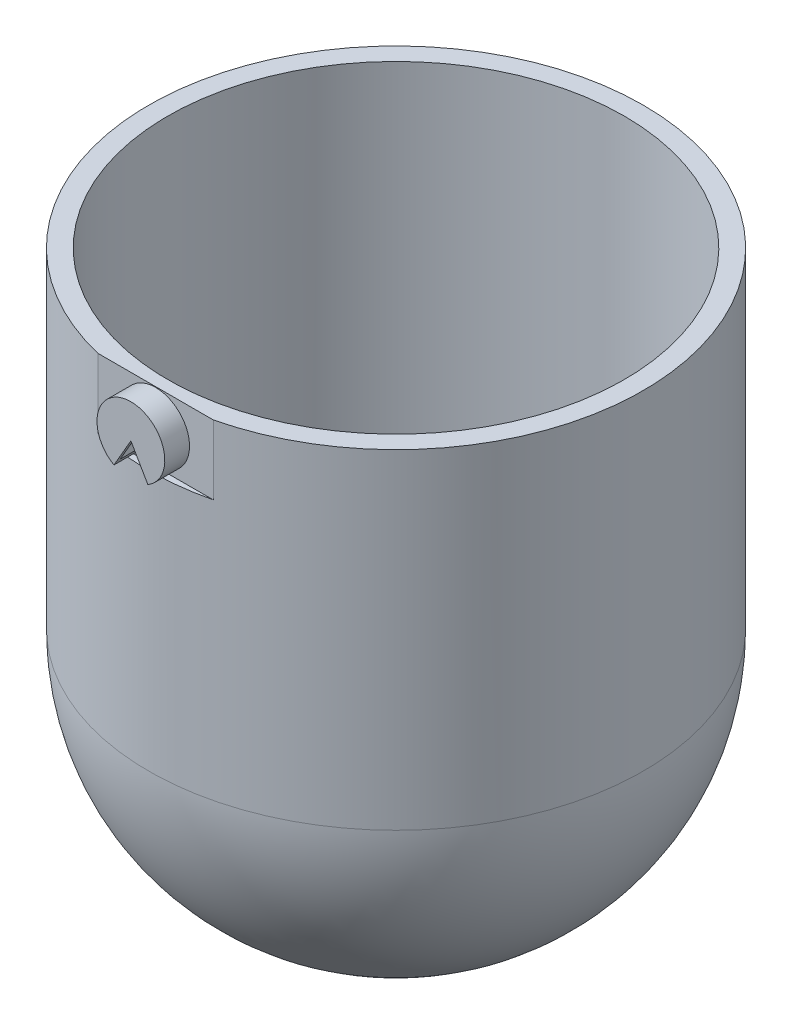
SolidWorks part; units mm, degrees
ref_plane "Front Plane" through (0, 0, 0) normal (0, 0, 1) x (1, 0, 0)
ref_plane "Top Plane" through (0, 0, 0) normal (0, 1, 0) x (1, 0, 0)
ref_plane "Right Plane" through (0, 0, 0) normal (1, 0, 0) x (0, 0, -1)
sketch "Sketch5" plane through (0, 0, 0) normal (0, 0, 1) x (1, 0, 0)
  line L6 (0, 0) -> (0, 50000) construction
  line L8 (-35.179, 0) -> (-35.179, 50.8)
  line L9 (-35.179, 50.8) -> (-38.1, 50.8)
  line L10 (-38.1, 50.8) -> (-38.1, 0)
  line L11 (0, -35.179) -> (0, -38.1)
  arc A4 (-38.1, 0) -> (0, -38.1) centre (0, 0) ccw
  arc A5 (-35.179, 0) -> (0, -35.179) centre (0, 0) ccw
revolve "Revolve4" add sketch "Sketch5" angle 360 about L6
ref_plane "Plane1" through (0, 0, 0) normal (0, 1, 0) x (1, 0, 0)
sketch "Sketch6" plane through (0, 0, 0) normal (0, 1, 0) x (1, 0, 0)
  circle A0 centre (-8.98, -11.9198) radius 0.7986
  circle A1 centre (-11.0264, 3.7524) radius 0.8984
  circle A2 centre (0.5032, -5.5311) radius 1.3015
  circle A3 centre (5.9935, 7.7953) radius 1.4509
  circle A4 centre (-3.34, 13.7847) radius 1.4552
  circle A5 centre (13.9794, -11.5205) radius 1.2185
  circle A6 centre (3.5478, -13.9163) radius 1.3476
  circle A7 centre (-13.7216, -5.5311) radius 1.4474
  circle A8 centre (10.4856, -1.1888) radius 1.5862
  circle A9 centre (-11.5754, 12.3295) radius 2.2017
  circle A10 centre (-3.34, 1.0073) radius 2.3046
  circle A11 centre (-3.34, -17.3602) radius 2.5016
  circle A12 centre (13.3305, 7.4958) radius 2.0046
  circle A13 centre (7.4444, 13.4353) radius 2.5494
  circle A14 centre (2.2002, 17.9273) radius 1.8168
  circle A15 centre (-0.495, 7.7953) radius 1.3769
  circle A16 centre (-4.7951, 5.9485) radius 1.7168
  circle A17 centre (-20.7092, 3.3119) radius 1.6651
  circle A18 centre (-15.6182, -12.7184) radius 2.545
  circle A19 centre (8.8993, -9.2745) radius 2.8944
  circle A20 centre (18.0222, -4.6327) radius 1.4577
  circle A21 centre (17.4732, 0.3974) radius 2.2817
  circle A22 centre (-14.8696, 7.6653) radius 1.4944
  circle A23 centre (-15.6182, 1.0073) radius 2.1475
  circle A24 centre (-7.3329, -4.6327) radius 2.1223
  circle A25 centre (5.9935, 0) radius 0.892
  circle A26 centre (4.5426, 2.1053) radius 0.9948
extrude "Cut-Extrude2" cut sketch "Sketch6" against normal through all both and the other way through all
ref_plane "Plane2" through (0, 53.34, 0) normal (0, 1, 0) x (1, 0, 0)
sketch "Sketch7" plane through (0, 53.34, 0) normal (0, 1, 0) x (1, 0, 0)
  line L0 (0, -38.1) -> (8.89, -38.1)
  line L1 (8.89, -38.1) -> (8.89, -37.0483)
  line L3 (0, -38.1) -> (-8.89, -38.1)
  line L4 (-8.89, -38.1) -> (-8.89, -37.0483)
  line L5 (8.89, -37.0483) -> (-8.89, -37.0483)
  circle A0 centre (0, 0) radius 38.1 construction
extrude "Cut-Extrude16" cut sketch "Sketch7" against normal blind 13.208
sketch "Sketch8" plane through (0, 0, 37.0483) normal (0, 0, 1) x (1, 0, 0)
  circle A0 centre (0, 45.466) radius 5.2257
extrude "Boss-Extrude1" add sketch "Sketch8" along normal blind 3.81 contours A0
sketch "Sketch9" plane through (0, 0, 40.8583) normal (0, 0, 1) x (1, 0, 0)
  line L0 (0, 45.466) -> (2.6129, 40.9404)
  line L1 (-2.6129, 40.9404) -> (0, 45.466)
  circle A1 centre (0, 45.466) radius 5.2257 construction
  arc A4 (-2.6129, 40.9404) -> (2.6129, 40.9404) centre (0, 45.466) ccw
extrude "Cut-Extrude17" cut sketch "Sketch9" against normal blind 3.81
sketch "Sketch10" plane through (0, 40.132, 0) normal (0, 1, 0) x (1, 0, 0)
  line L0 (0, -37.0016) -> (1.9406, -37.0016)
  line L1 (1.9406, -37.0016) -> (1.9406, -40.3036)
  line L2 (1.9406, -40.3036) -> (-2.2128, -40.3036)
  line L3 (-2.2128, -40.3036) -> (-2.2128, -37.0483)
  line L4 (8.89, -37.0483) -> (-8.89, -37.0483) construction
  line L5 (0, -37.0016) -> (-2.2128, -37.0483)
extrude "Cut-Extrude18" cut sketch "Sketch10" along normal blind 7.62
